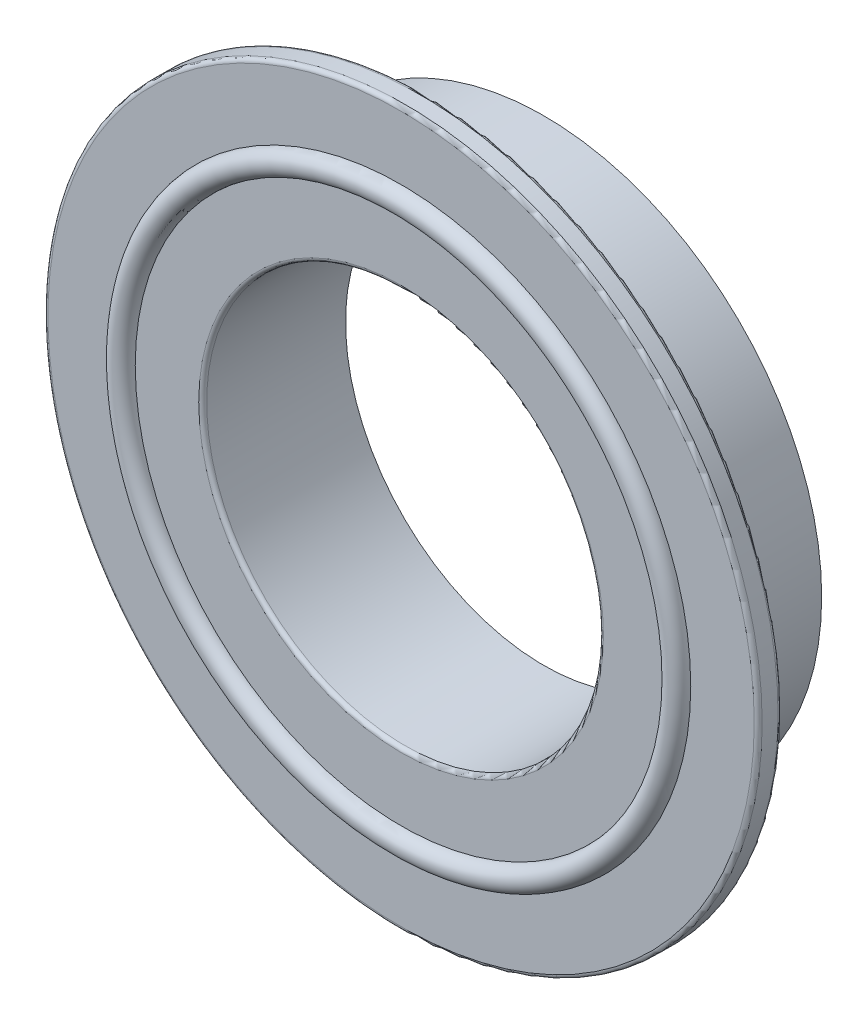
SolidWorks part; units mm, degrees
material "Zinc AG40A (Zn-4Al-0.4Mg; Zamak 3), Cast"
ref_plane "Front Plane" through (0, 0, 0) normal (1, 0, 0) x (0, 1, 0)
ref_plane "Top Plane" through (0, 0, 0) normal (0, 0, 1) x (0, 1, 0)
ref_plane "Right Plane" through (0, 0, 0) normal (0, 1, 0) x (-1, 0, 0)
sketch "Sketch1" plane through (0, 0, 0) normal (0, 0, 1) x (0, 1, 0)
  circle A0 centre (0, 0) radius 35
  circle A1 centre (0, 0) radius 25
  dimension "D1" = 70
  dimension "D2" = 50
extrude "Boss-Extrude1" add sketch "Sketch1" against normal blind 15
sketch "Sketch2" plane through (0, 0, 0) normal (0, 0, 1) x (1, 0, 0)
  line L0 (0, 0) -> (0, 45) construction
  line L1 (25, 0) -> (45, 0) construction
  circle A0 centre (0, 0) radius 25 construction
  circle A1 centre (0, 0) radius 25
  circle A2 centre (0, 0) radius 45
  dimension "D1" = 20
extrude "Boss-Extrude2" add sketch "Sketch2" along normal blind 3
sketch "Sketch3" plane through (0, 0, 0) normal (1, 0, 0) x (0, 1, 0)
  line L0 (45, 3) -> (-45, 3) construction
  line L1 (0, 13.0915) -> (0, -14.8171) construction
  circle A0 centre (-35, 3) radius 1.5
  dimension "D1" = 3
  dimension "D2" = 35
revolve "Revolve1" add sketch "Sketch3" angle 360 about L1
fillet "Fillet1" radius 0.5 3 edges at (45, 0, 0) (45, 0, 3) (25, 0, 3)
ref_plane "Plane1" through (0, 0, -5) normal (0, 0, -1) x (0, 1, 0)
sketch "Sketch4" plane through (0, 0, 0) normal (0, 0, 1) x (0, -1, 0)
  line L0 (0, 0) -> (0, 35) construction
  point P4 (0, 35)
  point P6 (35, 0)
  point P7 (0, -35)
  point P8 (-35, 0)
  point P9 (0, 0)
  dimension "D1" = 4
  dimension "D2" = 35
sketch "Sketch5" plane through (0, 0, -5) normal (0, 0, -1) x (0, 1, 0)
  line L0 (0, 0) -> (0, 35) construction
  line L1 (0, 0) -> (0, 35)
  circle A0 centre (0, 0) radius 35 construction
  circle A1 centre (0, 0) radius 35
  point P5 (0, 35)
ref_point "Point6"
ref_point "Point7" [suppressed]
ref_point "Point8" [suppressed]
ref_point "Point9" [suppressed]
ref_point "Point10"
ref_point "Point11"
ref_point "Point12"
ref_point "Point13"
